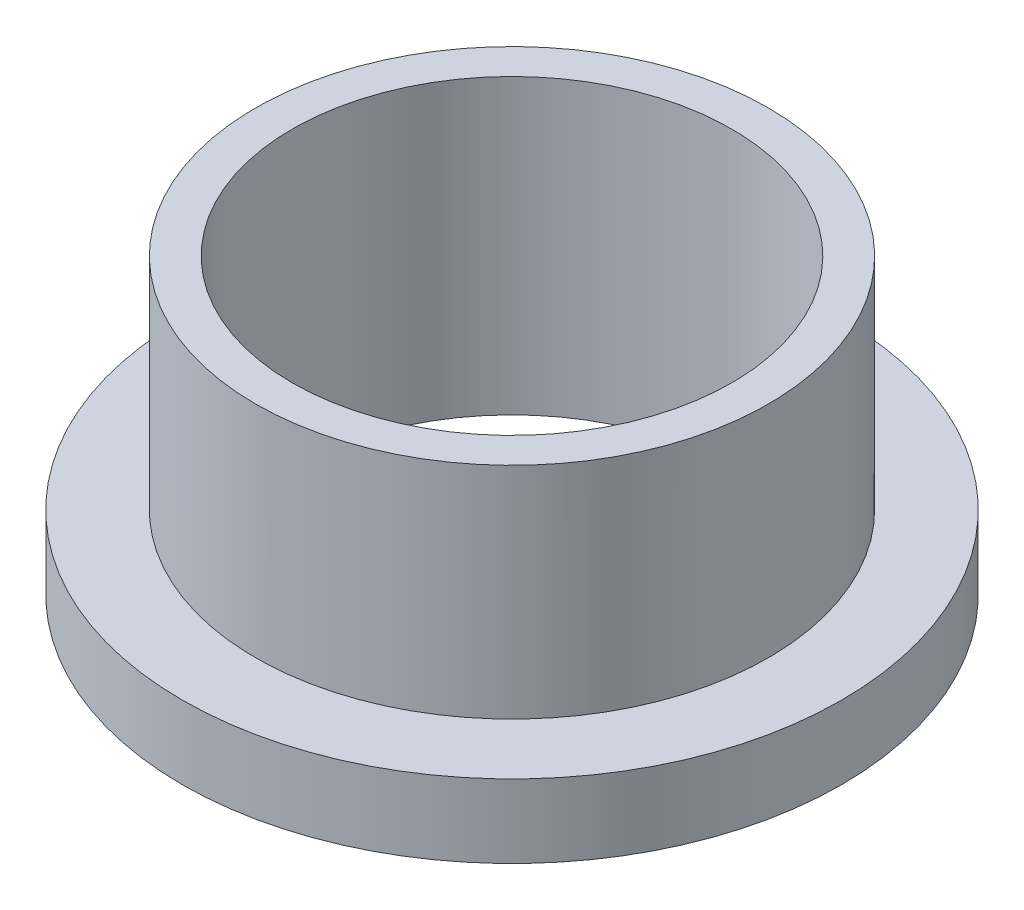
SolidWorks part; units mm, degrees
material "Commercial Bronze, UNS C22000 (90-10 Bronze)"
ref_plane "Front Plane" through (0, 0, 0) normal (0, 0, 1) x (1, 0, 0)
ref_plane "Top Plane" through (0, 0, 0) normal (0, 1, 0) x (1, 0, 0)
ref_plane "Right Plane" through (0, 0, 0) normal (1, 0, 0) x (0, 0, -1)
sketch "Sketch1" plane through (0, 0, 0) normal (0, 1, 0) x (1, 0, 0)
  circle A0 centre (0, 0) radius 9.525
  circle A1 centre (0, 0) radius 11.1125
  dimension "D1" = 19.05
  dimension "D2" = 22.225
extrude "Boss-Extrude1" add sketch "Sketch1" along normal blind 12.7
sketch "Sketch2" plane through (0, 0, 0) normal (0, -1, 0) x (1, 0, 0)
  circle A0 centre (0, 0) radius 11.1125 construction
  circle A1 centre (0, 0) radius 11.1125
  circle A2 centre (0, 0) radius 14.2875
  dimension "D1" = 28.575
extrude "Boss-Extrude2" add sketch "Sketch2" against normal blind 3.175
